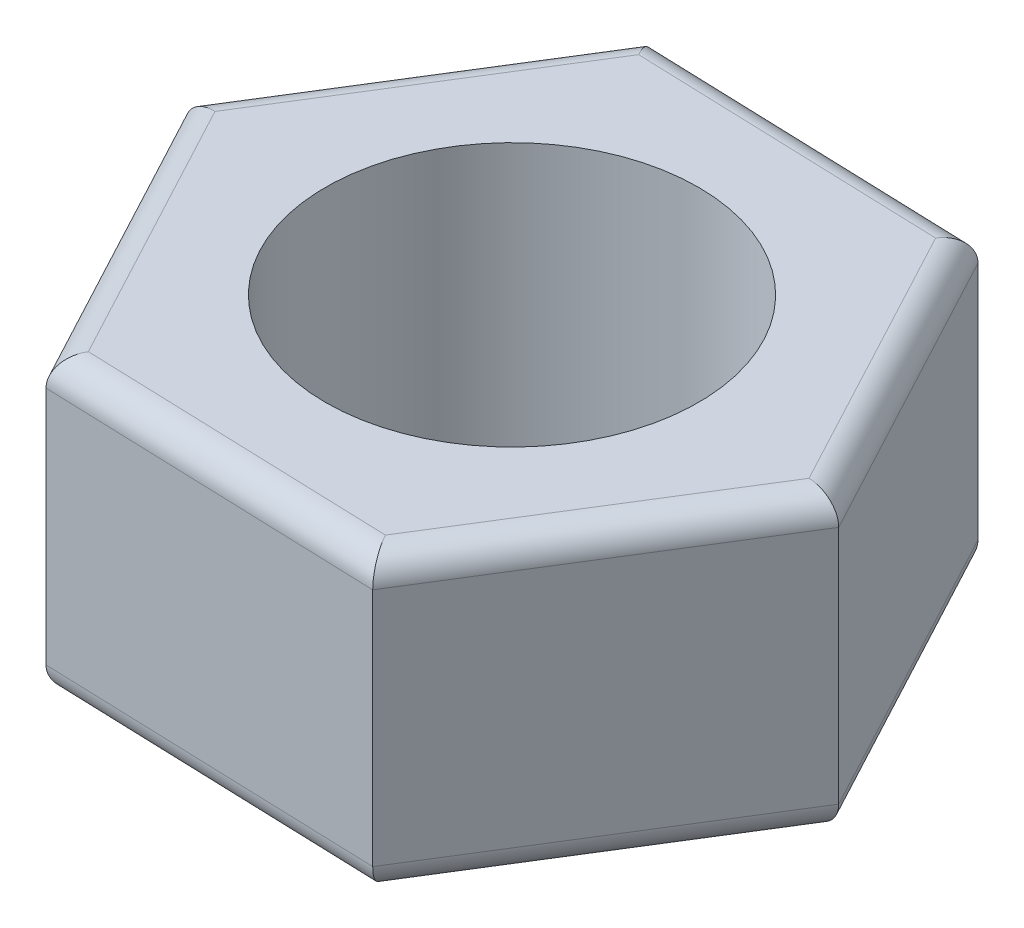
SolidWorks part; units mm, degrees
ref_plane "Front Plane" through (0, 0, 0) normal (0, 0, 1) x (1, 0, 0)
ref_plane "Top Plane" through (0, 0, 0) normal (0, 1, 0) x (1, 0, 0)
ref_plane "Right Plane" through (0, 0, 0) normal (1, 0, 0) x (0, 0, -1)
sketch "Sketch1" plane through (0, 0, 0) normal (0, 1, 0) x (1, 0, 0)
  line L1 (-12.6945, 0.4267) -> (-6.7168, -10.7804)
  line L2 (-6.7168, -10.7804) -> (5.9777, -11.2071)
  line L3 (5.9777, -11.2071) -> (12.6945, -0.4267)
  line L4 (12.6945, -0.4267) -> (6.7168, 10.7804)
  line L5 (6.7168, 10.7804) -> (-5.9777, 11.2071)
  line L6 (-5.9777, 11.2071) -> (-12.6945, 0.4267)
  circle A0 centre (0, 0) radius 7
  circle A1 centre (0, 0) radius 11 construction
  dimension "D2" = 14
  dimension "D1" = 22
extrude "Boss-Extrude1" add sketch "Sketch1" along normal blind 11
fillet "Fillet1" radius 1 12 edges at (9.3361, 0, 5.8169) (9.7057, 0, -5.1769) (0.3695, 0, -10.9938) (-9.3361, 0, -5.8169) (-9.7057, 0, 5.1769) (-0.3695, 0, 10.9938) (-0.3695, 11, 10.9938) (9.3361, 11, 5.8169) (9.7057, 11, -5.1769) (0.3695, 11, -10.9938) (-9.3361, 11, -5.8169) (-9.7057, 11, 5.1769)
